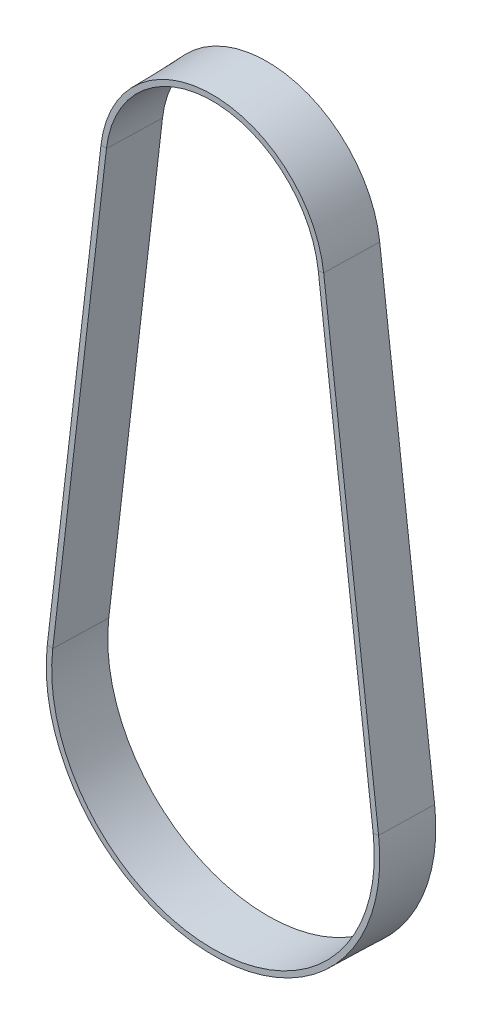
SolidWorks part; units mm, degrees
material "Rubber"
ref_plane "Front Plane" through (0, 0, 0) normal (0, 0, 1) x (1, 0, 0)
ref_plane "Top Plane" through (0, 0, 0) normal (0, 1, 0) x (1, 0, 0)
ref_plane "Right Plane" through (0, 0, 0) normal (1, 0, 0) x (0, 0, -1)
sketch "Sketch2" plane through (0, 0, 0) normal (0, 0, 1) x (1, 0, 0)
  line L0 (0, 0) -> (1, 0) construction
  line L1 (0, 0) -> (0, 1) construction
  line L2 (19.8588, 2.3724) -> (29.9014, -81.6913)
  line L3 (-29.6843, -81.7704) -> (-19.865, 2.3197)
  arc A0 (-19.865, 2.3197) -> (19.8588, 2.3724) centre (0, 0) cw
  arc A1 (29.9014, -81.6913) -> (-29.6843, -81.7704) centre (0.1132, -85.2499) cw
ref_plane "Plane1" through (19.8588, 2.3724, 0) normal (0.1186, -0.9929, 0) x (-0.9929, -0.1186, 0)
sketch "Sketch3" plane through (19.8588, 2.3724, 0) normal (0.1186, -0.9929, 0) x (-0.9929, -0.1186, 0)
  line L0 (0.75, 10) -> (-0.75, 10)
  line L1 (-0.75, 10) -> (-0.5, 0)
  line L2 (-0.5, 0) -> (0.5, 0)
  line L3 (0.5, 0) -> (0.75, 10)
  point P5 (0, 0)
  dimension "D1" = 1.5
  dimension "D2" = 10
  dimension "D3" = 1
sweep "Sweep1" add profiles "Sketch3" path "Sketch2"
